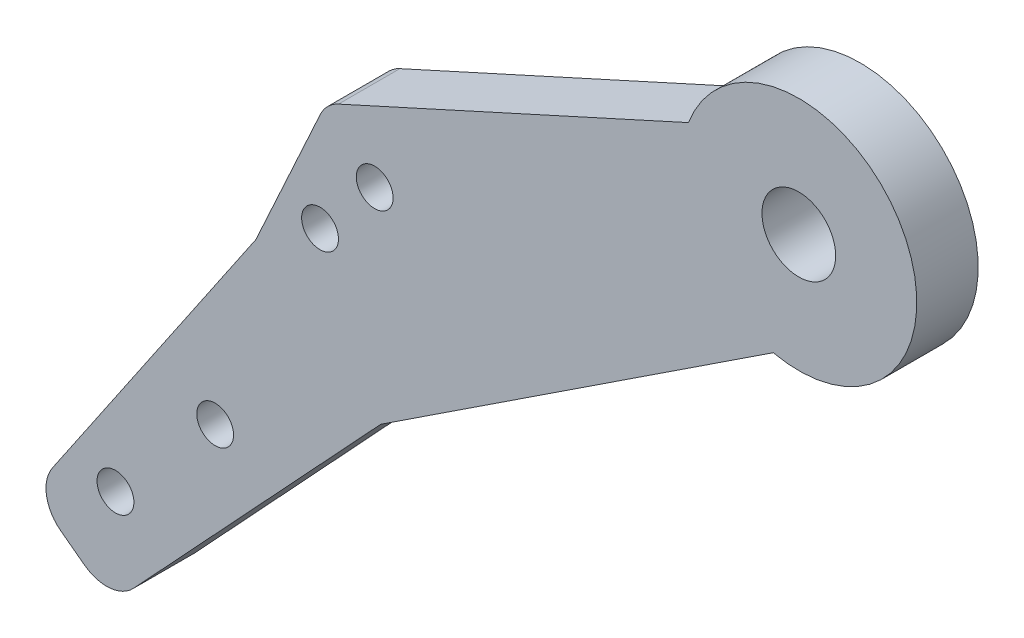
SolidWorks part; units mm, degrees
ref_plane "前视基准面" through (0, 0, 0) normal (0, 0, 1) x (1, 0, 0)
ref_plane "上视基准面" through (0, 0, 0) normal (0, 1, 0) x (1, 0, 0)
ref_plane "右视基准面" through (0, 0, 0) normal (1, 0, 0) x (0, 0, -1)
sketch "草图1" plane through (0, 0, 0) normal (0, 0, 1) x (1, 0, 0)
  line L0 (-34.0325, -30.3971) -> (-55.9954, -53.999)
  line L1 (-2.0809, -9.3769) -> (-34.0325, -30.3971)
  line L2 (-62.3744, -49.2118) -> (-44.1951, -22.4522)
  line L4 (-55.9954, -53.999) -> (-34.0325, -30.3971)
  line L5 (-55.9954, -53.999) -> (-62.3744, -49.2118)
  line L9 (-44.1951, -22.4522) -> (-38.4948, -10.0084)
  line L10 (-38.4948, -10.0084) -> (-8.985, 3.3951)
  line L11 (9.605, 0) -> (9.605, -35.8716) construction
  arc A0 (-2.0809, -9.3769) -> (-8.985, 3.3951) centre (0, 0) ccw
  circle A1 centre (-55.6302, -45.944) radius 1.5
  circle A2 centre (-47.5127, -37.1473) radius 1.5
  circle A3 centre (-34.5273, -13.9429) radius 1.5
  circle A4 centre (-38.9755, -19.0619) radius 1.5
  dimension "D1" = 38.246
  dimension "D3" = 19.21
  dimension "D15" = 3
  dimension "D16" = 6.6618
  dimension "D17" = 18.57
  dimension "D18" = 5.27
  dimension "D19" = 3
  dimension "D20" = 3.3334
  dimension "D21" = 8.0443
  dimension "D22" = 3
  dimension "D23" = 3
  dimension "D24" = 5.223
  dimension "D25" = 5.2457
  dimension "D14" = 5.22
  dimension "D2" = 6.69
  dimension "D4" = 32.4112
  dimension "D5" = 166.28
  dimension "D6" = 32.3507
  dimension "D7" = 32.24
  dimension "D8" = 7.9754
  dimension "D9" = 13.6873
  dimension "D10" = 6.8068
  dimension "D11" = 56.66
  dimension "D12" = 92.696
  dimension "D13" = 65.572
extrude "凸台-拉伸1" add sketch "草图1" along normal blind 5 contours L1 A0 L10 L9 L2 L5 L0 A4 A3 A2 A1
fillet "圆角1" radius 3 1 edges at (-55.9954, -53.999, 2.5)
fillet "圆角2" radius 3 1 edges at (-62.3744, -49.2118, 2.5)
fillet "圆角3" radius 3 1 edges at (-38.4948, -10.0084, 2.5)
sketch "草图4" plane through (0, 0, 5) normal (0, 0, 1) x (1, 0, 0)
  circle A0 centre (0, 0) radius 3
extrude "切除-拉伸1" cut sketch "草图4" against normal through all
